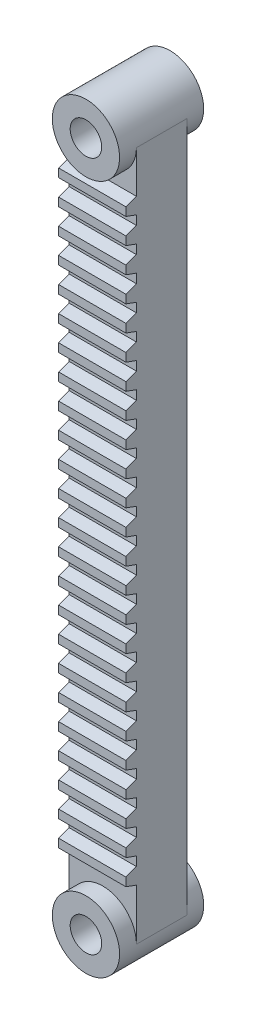
SolidWorks part; units mm, degrees
ref_plane "Front Plane" through (0, 0, 0) normal (1, 0, 0) x (0, 1, 0)
ref_plane "Top Plane" through (0, 0, 0) normal (0, 0, 1) x (0, 1, 0)
ref_plane "Right Plane" through (0, 0, 0) normal (0, 1, 0) x (-1, 0, 0)
sketch "Sketch1" plane through (0, 0, 0) normal (0, 0, 1) x (0, 1, 0)
  line L0 (0, 26.4605) -> (0, 8.1752) construction
  circle A0 centre (-82, 0) radius 8
  circle A1 centre (-82, 0) radius 3.75
  circle A2 centre (82, 0) radius 3.75
  circle A3 centre (82, 0) radius 8
  dimension "D1" = 16
  dimension "D3" = 7.5
  dimension "D2" = 164
extrude "Boss-Extrude1" add sketch "Sketch1" along normal mid plane 20
sketch "Sketch2" plane through (0, 0, 0) normal (0, 0, 1) x (0, 1, 0)
  line L1 (-82, 8) -> (82, 8)
  line L2 (-82, 8) -> (-82, -8)
  line L3 (-82, -8) -> (82, -8)
  line L4 (82, 8) -> (82, -8)
  circle A0 centre (-82, 0) radius 8 construction
  circle A1 centre (82, 0) radius 8 construction
  circle A2 centre (-82, 0) radius 3.75 construction
  circle A4 centre (-82, 0) radius 8
  circle A5 centre (-82, 0) radius 8
  circle A6 centre (82, 0) radius 8
  circle A7 centre (82, 0) radius 8
  point P8 (-77.6721, 6.7282)
  point P9 (-82, 0)
  dimension "D1" = 0
  dimension "D2" = 0
extrude "Boss-Extrude2" add sketch "Sketch2" along normal mid plane 12 contours L4 L1 L2 L3
sketch "Sketch3" plane through (8, 0, 0) normal (1, 0, 0) x (0, 1, 0)
  line L0 (72, 6) -> (71.0901, 8.5)
  line L1 (-82, 6) -> (82, 6) construction
  line L2 (71.0901, 8.5) -> (69.0901, 8.5)
  line L3 (69.0901, 8.5) -> (68.1801, 6)
  line L4 (68.1801, 6) -> (72, 6)
  line L5 (90, -10) -> (90, 10) construction
  point P4 (70.0901, 6)
  point P7 (70.0901, 8.5)
  dimension "D1" = 18
  dimension "D2" = 2
  dimension "D3" = 40
  dimension "D4" = 2.5
extrude "Boss-Extrude3" add sketch "Sketch3" against normal up to surface (16 mm away) up to face at (-8, 0, 0)
pattern_linear "LPattern1" count 24 spacing 6 along (0, -1, 0) of "Boss-Extrude3"
